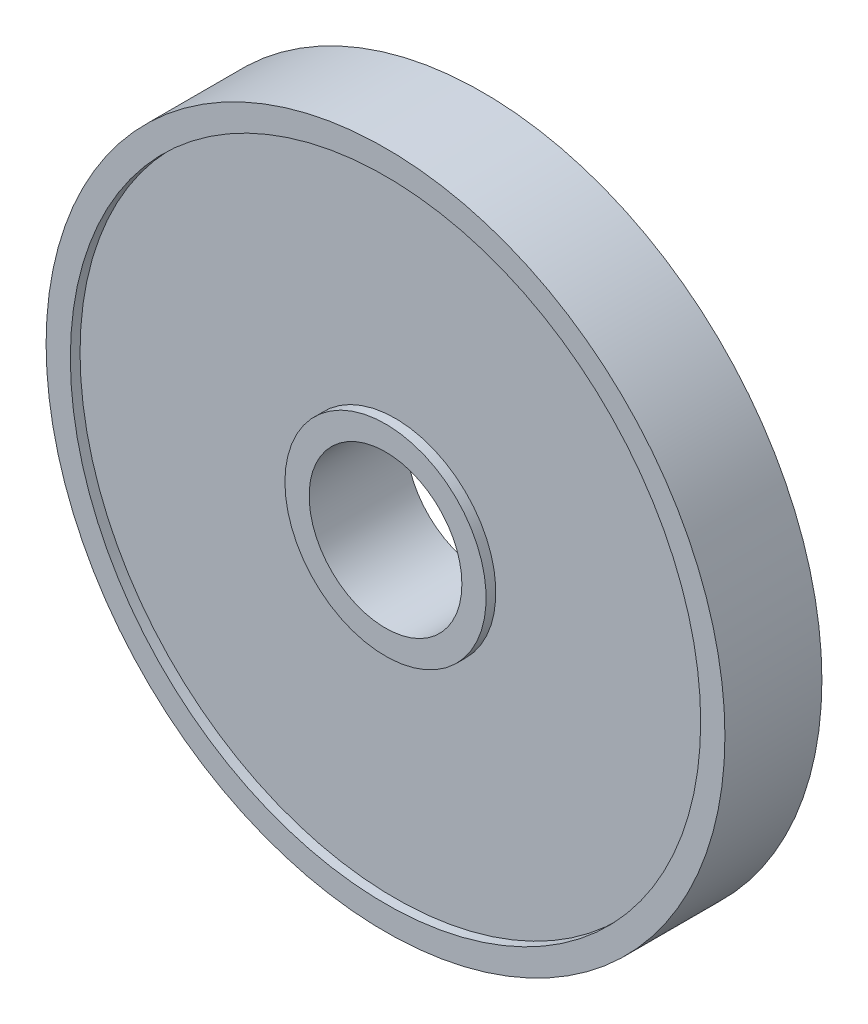
SolidWorks part; units mm, degrees
material "Cast Iron"
ref_plane "Front" through (0, 0, 0) normal (0, 0, 1) x (1, 0, 0)
ref_plane "Top" through (0, 0, 0) normal (0, 1, 0) x (1, 0, 0)
ref_plane "Right" through (0, 0, 0) normal (1, 0, 0) x (0, 0, -1)
sketch "Skizze1" plane through (0, 0, 0) normal (0, 0, 1) x (1, 0, 0)
  circle A0 centre (0, 0) radius 15.75
  circle A1 centre (0, 0) radius 70
  dimension "D1" = 31.5
  dimension "D2" = 140
extrude "Aufsatz-Linear austragen1" add sketch "Skizze1" along normal blind 20
sketch "Skizze2" plane through (0, 0, 0) normal (1, 0, 0) x (0, 0, -1)
  line L0 (0, 0) -> (-20, 0) construction
  line L1 (-20, 70) -> (-20, -70) construction
  line L2 (-10, 0) -> (-10, 69.9006) construction
  line L3 (-20, 20.75) -> (-20, 65)
  line L4 (-20, 65) -> (-18, 65)
  line L5 (-18, 65) -> (-18, 20.75)
  line L6 (-18, 20.75) -> (-20, 20.75)
  line L7 (-2, 20.75) -> (0, 20.75)
  line L8 (-2, 65) -> (-2, 20.75)
  line L9 (0, 65) -> (-2, 65)
  line L10 (0, 20.75) -> (0, 65)
  line L12 (0, 70) -> (-10, 70) construction
  line L13 (0, 70) -> (-20, 70) construction
  dimension "D1" = 20.75
  dimension "D2" = 5
  dimension "D3" = 2
revolve "Schnitt-Rotation1" cut sketch "Skizze2" angle 360 about L0
